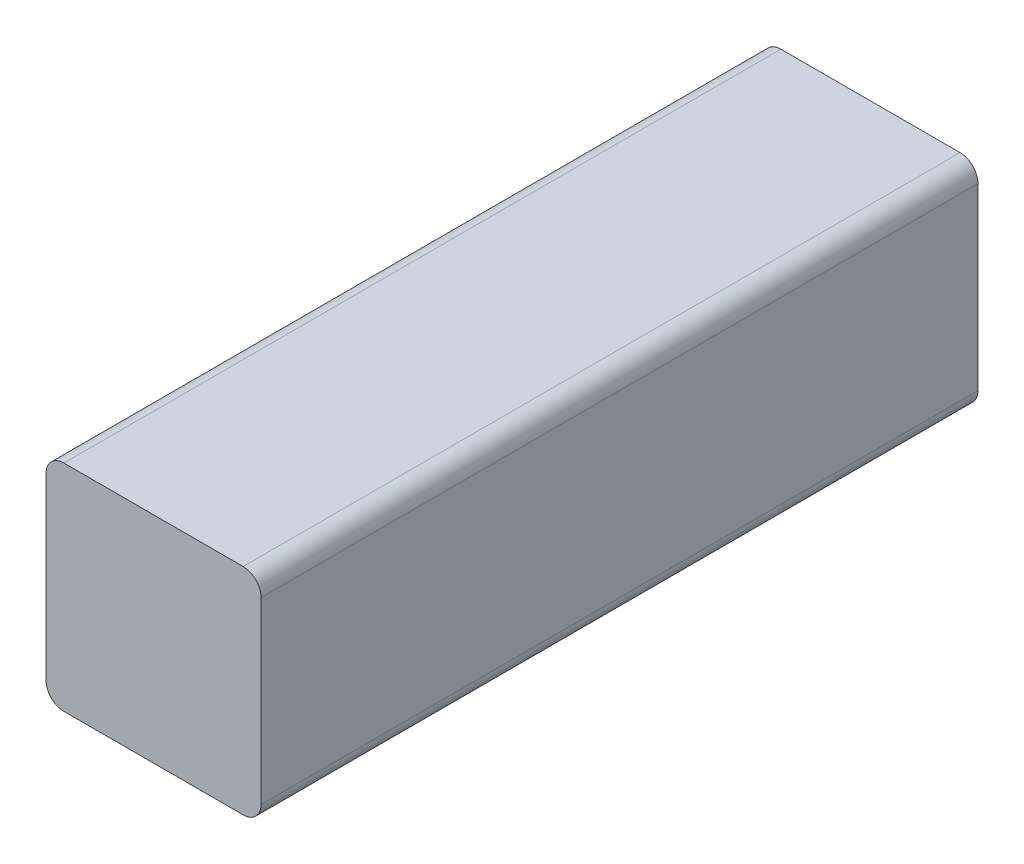
SolidWorks part; units mm, degrees
ref_plane "Plano frontal" through (0, 0, 0) normal (0, 0, 1) x (1, 0, 0)
ref_plane "Plano superior" through (0, 0, 0) normal (0, 1, 0) x (1, 0, 0)
ref_plane "Plano direito" through (0, 0, 0) normal (1, 0, 0) x (0, 0, -1)
sketch "Esboço1" plane through (0, 0, 0) normal (0, 0, 1) x (1, 0, 0)
  line L1 (2.5, 11.3) -> (-2.5, 11.3)
  line L2 (3, 10.8) -> (3, 5.8)
  line L3 (2.5, 5.3) -> (-2.5, 5.3)
  line L4 (-3, 10.8) -> (-3, 5.8)
  arc A0 (-2.5, 11.3) -> (-3, 10.8) centre (-2.5, 10.8) ccw
  arc A1 (2.5, 11.3) -> (3, 10.8) centre (2.5, 10.8) cw
  arc A2 (3, 5.8) -> (2.5, 5.3) centre (2.5, 5.8) cw
  arc A3 (-2.5, 5.3) -> (-3, 5.8) centre (-2.5, 5.8) cw
  point P10 (3, 11.3)
  point P15 (-3, 5.3)
  dimension "D1" = 0.5
extrude "Ressalto-extrusão1" add sketch "Esboço1" against normal up to vertex (20 mm away)
